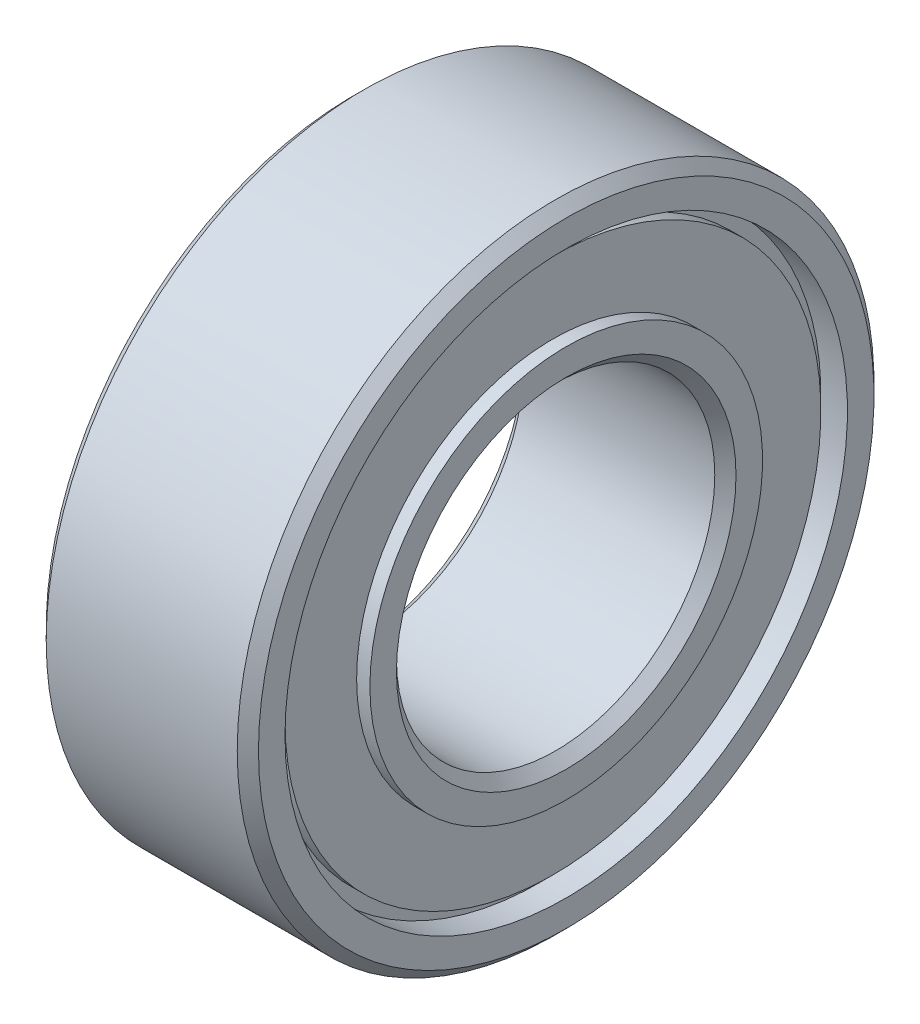
SolidWorks part; units mm, degrees
ref_plane "前视基准面" through (0, 0, 0) normal (0, 0, 1) x (1, 0, 0)
ref_plane "上视基准面" through (0, 0, 0) normal (0, 1, 0) x (1, 0, 0)
ref_plane "右视基准面" through (0, 0, 0) normal (1, 0, 0) x (0, 0, -1)
other "Configuration Table"
sketch "草图1" plane through (0, 0, 0) normal (0, 0, 1) x (1, 0, 0)
  line L0 (-3.901, 0) -> (3.7973, 0) construction
  line L1 (0, 7.17) -> (0, -5.7744) construction
  line L2 (-2, 3) -> (2, 3)
  line L3 (2, 3) -> (2, 3.7)
  line L4 (2, 3.7) -> (1.75, 3.7)
  line L5 (1.75, 3.7) -> (1.75, 5.05)
  line L6 (1.75, 5.05) -> (1.5, 5.05)
  line L7 (1.5, 5.05) -> (1.5, 5.3)
  line L8 (1.5, 5.3) -> (2, 5.3)
  line L9 (2, 5.3) -> (2, 6)
  line L10 (2, 6) -> (-2, 6)
  line L11 (-2, 5.3) -> (-2, 6)
  line L12 (-1.5, 5.3) -> (-2, 5.3)
  line L13 (-1.5, 5.05) -> (-1.5, 5.3)
  line L14 (-1.75, 5.05) -> (-1.5, 5.05)
  line L15 (-1.75, 3.7) -> (-1.75, 5.05)
  line L16 (-2, 3.7) -> (-1.75, 3.7)
  line L17 (-2, 3) -> (-2, 3.7)
  point P6 (-2, 3.35)
  point P16 (0, 6)
  point P23 (0, 3)
  dimension "D1" = 3
  dimension "D2" = 0.7
  dimension "D3" = 6
  dimension "D4" = 0.7
  dimension "D5" = 0.25
  dimension "D6" = 4
  dimension "D7" = 0.25
  dimension "D8" = 0.5
revolve "旋转1" add sketch "草图1" angle 360 about L0
chamfer "倒角1" distance 0.2 angle 45 4 edges at (2, 0, 6) (-2, 0, 6) (-2, 0, 3) (2, 0, 3)
